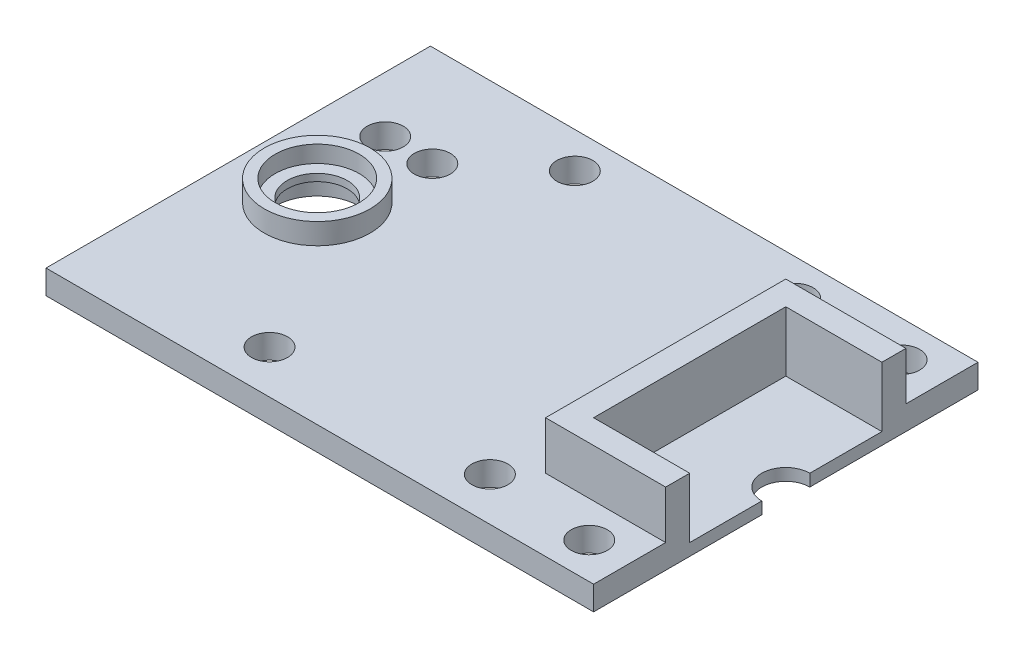
SolidWorks part; units mm, degrees
ref_plane "Front Plane" through (0, 0, 0) normal (0, 0, 1) x (1, 0, 0)
ref_plane "Top Plane" through (0, 0, 0) normal (0, 1, 0) x (1, 0, 0)
ref_plane "Right Plane" through (0, 0, 0) normal (1, 0, 0) x (0, 0, -1)
sketch "Sketch1" plane through (0, 0, 0) normal (0, 1, 0) x (1, 0, 0)
  line L1 (-279.4, -50.8) -> (0, -50.8)
  line L2 (-279.4, -50.8) -> (-279.4, 50.8)
  line L3 (-279.4, 50.8) -> (0, 50.8)
  line L4 (0, -50.8) -> (0, 50.8)
  point P0 (0, 0)
  dimension "D1" = 279.4
  dimension "D2" = 101.6
  dimension "D3" = 50.8
extrude "Boss-Extrude1" add sketch "Sketch1" along normal blind 6.35
sketch "Sketch2" plane through (0, 6.35, 0) normal (0, 1, 0) x (1, 0, 0)
  line L0 (-279.4, 50.8) -> (-279.4, -50.8) construction
  line L2 (0, 50.8) -> (-279.4, 50.8) construction
  circle A0 centre (-258.5106, 0) radius 13.97
  dimension "D1" = 50.8
  dimension "D2" = 27.94
  dimension "D3" = 20.8894
extrude "Boss-Extrude3" add sketch "Sketch2" along normal blind 5.5562
sketch "Sketch9" plane through (0, 11.9062, 0) normal (0, 1, 0) x (1, 0, 0)
  circle A0 centre (-258.5106, 0) radius 11.1125
  dimension "D1" = 22.225
extrude "Cut-Extrude4" cut sketch "Sketch9" against normal blind 4.445
sketch "Sketch10" plane through (0, 0, 0) normal (0, -1, 0) x (-1, 0, 0)
  circle A0 centre (258.5106, 0) radius 11.1125
  dimension "D1" = 22.225
extrude "Cut-Extrude5" cut sketch "Sketch10" against normal blind 5.5562
sketch "Sketch11" plane through (0, 7.4613, 0) normal (0, 1, 0) x (1, 0, 0)
  circle A0 centre (-258.5106, 0) radius 7.9375
  dimension "D1" = 15.875
extrude "Cut-Extrude6" cut sketch "Sketch11" against normal through all
sketch "Sketch12" plane through (0, 6.35, 0) normal (0, 1, 0) x (1, 0, 0)
  line L0 (0, 50.8) -> (-279.4, 50.8) construction
  line L1 (-279.4, 50.8) -> (-279.4, -50.8) construction
  circle A0 centre (-134.6662, 0) radius 6.35
  dimension "D1" = 12.7
  dimension "D2" = 50.8
  dimension "D3" = 144.7338
extrude "Cut-Extrude7" cut sketch "Sketch12" against normal through all
sketch "Sketch22" plane through (0, 6.35, 0) normal (0, 1, 0) x (1, 0, 0)
  line L1 (-102.9162, -31.75) -> (-166.4162, -31.75)
  line L2 (-102.9162, -31.75) -> (-102.9162, 31.75)
  line L3 (-102.9162, 31.75) -> (-166.4162, 31.75)
  line L4 (-166.4162, -31.75) -> (-166.4162, 31.75)
  line L5 (-102.9162, -31.75) -> (-166.4162, 31.75) construction
  line L6 (-102.9162, 31.75) -> (-166.4162, -31.75) construction
  circle A0 centre (-134.6662, 0) radius 6.35 construction
  point P0 (-134.6662, 0)
  dimension "D1" = 63.5
  dimension "D2" = 63.5
extrude "Boss-Extrude7" add sketch "Sketch22" along normal blind 12.7
sketch "Sketch25" plane through (0, 19.05, 0) normal (0, 1, 0) x (1, 0, 0)
  line L1 (-109.2662, -25.4) -> (-160.0662, -25.4)
  line L2 (-109.2662, -25.4) -> (-109.2662, 25.4)
  line L3 (-109.2662, 25.4) -> (-160.0662, 25.4)
  line L4 (-160.0662, -25.4) -> (-160.0662, 25.4)
  line L5 (-109.2662, -25.4) -> (-160.0662, 25.4) construction
  line L6 (-109.2662, 25.4) -> (-160.0662, -25.4) construction
  circle A0 centre (-134.6662, 0) radius 6.35 construction
  point P0 (-134.6662, 0)
  dimension "D1" = 50.8
  dimension "D2" = 50.8
extrude "Cut-Extrude11" cut sketch "Sketch25" against normal blind 15.875
sketch "Sketch32" plane through (0, 6.35, 0) normal (0, 1, 0) x (1, 0, 0)
  line L0 (0, -50.8) -> (0, 50.8) construction
  line L3 (-279.4, -50.8) -> (0, -50.8) construction
  line L5 (0, 50.8) -> (-279.4, 50.8) construction
  circle A0 centre (-67.442, -40.64) radius 4.7625
  circle A1 centre (-81.412, -40.64) radius 4.7625
  circle A2 centre (-67.442, 40.64) radius 4.7625
  circle A3 centre (-81.412, 40.64) radius 4.7625
  dimension "D1" = 10.16
  dimension "D2" = 10.16
  dimension "D3" = 10.16
  dimension "D4" = 10.16
  dimension "D9" = 9.525
  dimension "D10" = 9.525
  dimension "D11" = 9.525
  dimension "D12" = 9.525
  dimension "D5" = 13.97
  dimension "D6" = 13.97
  dimension "D7" = 81.28
  dimension "D8" = 81.412
extrude "Cut-Extrude12" cut sketch "Sketch32" against normal blind 6.35
sketch "Sketch38" plane through (0, 6.35, 0) normal (0, 1, 0) x (1, 0, 0)
  line L0 (0, -50.8) -> (0, 50.8) construction
  line L1 (0, -34.0128) -> (-46.99, -34.0128)
  line L2 (0, -34.0128) -> (0, -15.5426)
  line L3 (0, -15.5426) -> (-46.99, -15.5426)
  line L4 (-46.99, -34.0128) -> (-46.99, -15.5426)
  line L6 (-279.4, -50.8) -> (0, -50.8) construction
  dimension "D1" = 35.2574
  dimension "D2" = 18.4703
  dimension "D3" = 46.99
extrude "Cut-Extrude13" cut sketch "Sketch38" against normal blind 6.35
sketch "Sketch60" plane through (0, 6.35, 0) normal (0, 1, 0) x (1, 0, 0)
  line L1 (-279.4, 50.8) -> (-279.4, -50.8) construction
  line L2 (0, 50.8) -> (-279.4, 50.8) construction
  circle A0 centre (-231.7492, 41.3241) radius 4.7625
  circle A1 centre (-231.7492, -39.3693) radius 4.7625
  circle A2 centre (-173.5092, -39.3693) radius 4.7625
  circle A3 centre (-173.5092, 41.3241) radius 4.7625
  dimension "D1" = 47.6508
  dimension "D5" = 9.525
  dimension "D6" = 9.525
  dimension "D7" = 9.525
  dimension "D8" = 9.525
  dimension "D2" = 58.24
  dimension "D3" = 80.6935
  dimension "D4" = 9.4759
  dimension "D9" = 105.8908
extrude "Cut-Extrude23" cut sketch "Sketch60" against normal up to surface (6.35 mm away) up to face at (-81.5975, 0, 12.3889)
sketch "Sketch64" plane through (0, 6.35, 0) normal (0, 1, 0) x (1, 0, 0)
  line L0 (-279.4, -50.8) -> (0, -50.8) construction
  circle A0 centre (-145.3342, -41.275) radius 4.7625
  circle A1 centre (-123.9982, -41.275) radius 4.7625
  circle A3 centre (-134.6662, 0) radius 6.35 construction
  dimension "D1" = 21.336
  dimension "D3" = 9.525
  dimension "D4" = 9.525
  dimension "D2" = 10.668
  dimension "D5" = 9.525
  dimension "D6" = 9.525
extrude "Cut-Extrude24" cut sketch "Sketch64" against normal through all
mirror "Mirror1" about plane through (0, 0, 0) normal (0, 0, 1) of "Cut-Extrude24"
sketch "Sketch69" plane through (0, 0, 50.8) normal (0, 0, 1) x (1, 0, 0)
  line L0 (-279.4, 6.35) -> (0, 6.35) construction
  line L1 (-86.9754, 6.35) -> (-53.9554, 6.35)
  line L2 (-86.9754, 6.35) -> (-86.9754, 0)
  line L3 (-86.9754, 0) -> (-53.9554, 0)
  line L4 (-53.9554, 6.35) -> (-53.9554, 0)
  line L5 (-279.4, 0) -> (0, 0) construction
  line L7 (0, 6.35) -> (0, 0) construction
  dimension "D1" = 33.02
  dimension "D2" = 53.9554
extrude "Boss-Extrude10" add sketch "Sketch69" along normal blind 19.05
sketch "Sketch70" plane through (0, 6.35, 0) normal (0, 1, 0) x (1, 0, 0)
  line L1 (-86.9754, -69.85) -> (-86.9754, -50.8) construction
  circle A0 centre (-76.8154, -60.325) radius 4.7625
  circle A1 centre (-64.1154, -60.325) radius 2.54
  point P6 (-86.9754, -60.325)
  dimension "D1" = 9.525
  dimension "D3" = 5.08
  dimension "D2" = 10.16
  dimension "D4" = 22.86
extrude "Cut-Extrude26" cut sketch "Sketch70" against normal up to surface (6.35 mm away) up to face at (-145.3342, 0, -46.0375)
mirror "Mirror2" about plane through (0, 0, 0) normal (0, 0, 1) of "Cut-Extrude26", "Boss-Extrude10"
sketch "Sketch76" plane through (0, 6.35, 0) normal (0, 1, 0) x (1, 0, 0)
  line L0 (-279.4, 50.8) -> (-279.4, -50.8) construction
  line L1 (-86.9754, 50.8) -> (-279.4, 50.8) construction
  circle A0 centre (-264.668, 24.13) radius 4.7625
  circle A1 centre (-252.222, 24.13) radius 4.7625
  dimension "D1" = 14.732
  dimension "D2" = 12.446
  dimension "D3" = 9.525
  dimension "D4" = 9.525
  dimension "D5" = 26.67
  dimension "D6" = 26.67
extrude "Cut-Extrude29" cut sketch "Sketch76" against normal up to surface (6.35 mm away) up to face at (-76.8154, 0, -65.0875)
sketch "Sketch77" plane through (0, 6.35, 0) normal (0, 1, 0) x (1, 0, 0)
  line L0 (-53.9554, -50.8) -> (0, -50.8) construction
  line L1 (0, -34.0128) -> (-46.99, -34.0128)
  line L2 (0, -34.0128) -> (0, -50.8)
  line L3 (0, -50.8) -> (-46.99, -50.8)
  line L4 (-46.99, -34.0128) -> (-46.99, -50.8)
  line L5 (-46.99, -15.5426) -> (-46.99, -34.0128) construction
extrude "Cut-Extrude30" cut sketch "Sketch77" against normal up to surface (6.35 mm away) up to face at (-264.668, 0, -28.8925)
sketch "Sketch78" plane through (0, 6.35, 0) normal (0, 1, 0) x (1, 0, 0)
  line L0 (0, -15.5426) -> (-46.99, -15.5426) construction
  line L1 (-49.276, -15.5426) -> (0, -15.5426)
  line L2 (-49.276, -15.5426) -> (-49.276, 50.8)
  line L3 (-49.276, 50.8) -> (0, 50.8)
  line L4 (0, -15.5426) -> (0, 50.8)
  dimension "D1" = 49.276
extrude "Cut-Extrude32" cut sketch "Sketch78" against normal blind 1.524 contours L2 L1 L4 L3
sketch "Sketch79" plane through (0, 4.826, 0) normal (0, 1, 0) x (1, 0, 0)
  line L0 (-46.99, -15.5426) -> (0, -15.5426) construction
  line L1 (0, -15.5426) -> (0, 50.8) construction
  circle A0 centre (-23.876, 15.1914) radius 4.7625
  dimension "D3" = 9.525
  dimension "D1" = 30.734
  dimension "D2" = 23.876
extrude "Cut-Extrude33" cut sketch "Sketch79" against normal up to surface (4.826 mm away) up to face at (-86.8931, 0, 2.2204)
sketch "Sketch80" plane through (0, 3.175, 0) normal (0, 1, 0) x (1, 0, 0)
  line L0 (-134.6662, 0) -> (-134.6662, -50.8)
  line L1 (-134.6662, 0) -> (-134.6662, 50.8)
  line L2 (-86.9754, 50.8) -> (-279.4, 50.8) construction
  line L3 (-279.4, -50.8) -> (-86.9754, -50.8) construction
  point P3 (0, 0)
  point P7 (0, 0)
  point P8 (0, 0)
extrude "Cut-Extrude34" cut sketch "Sketch80" against normal through all and the other way through all flip side to cut
